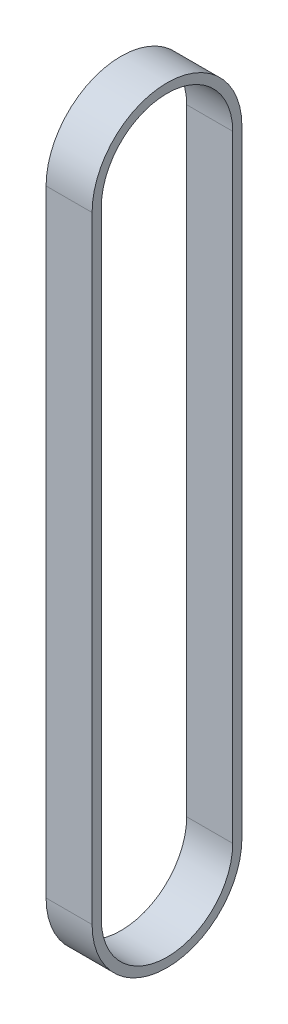
SolidWorks part; units mm, degrees
ref_plane "Front Plane" through (0, 0, 0) normal (0, 0, 1) x (1, 0, 0)
ref_plane "Top Plane" through (0, 0, 0) normal (0, 1, 0) x (1, 0, 0)
ref_plane "Right Plane" through (0, 0, 0) normal (1, 0, 0) x (0, 0, -1)
sketch "Sketch1" plane through (0, 0, 0) normal (1, 0, 0) x (0, 0, -1)
  line L0 (4.5339, 0) -> (4.5339, -42.545)
  line L1 (-4.5339, -42.545) -> (-4.5339, 0)
  line L2 (0, -42.545) -> (0, 0) construction
  line L3 (5.1689, 0) -> (5.1689, -42.545)
  line L4 (-5.1689, -42.545) -> (-5.1689, 0)
  arc A0 (-4.5339, 0) -> (4.5339, 0) centre (0, 0) cw
  arc A1 (-5.1689, 0) -> (5.1689, 0) centre (0, 0) cw
  arc A2 (4.5339, -42.545) -> (-4.5339, -42.545) centre (0, -42.545) cw
  arc A3 (5.1689, -42.545) -> (-5.1689, -42.545) centre (0, -42.545) cw
  dimension "D2" = 0.635
  dimension "D3" = 0.635
  dimension "D4" = 4.5339
  dimension "D5" = 4.5339
  dimension "D1" = 42.545
extrude "Boss-Extrude1" add sketch "Sketch1" along normal blind 3.175
